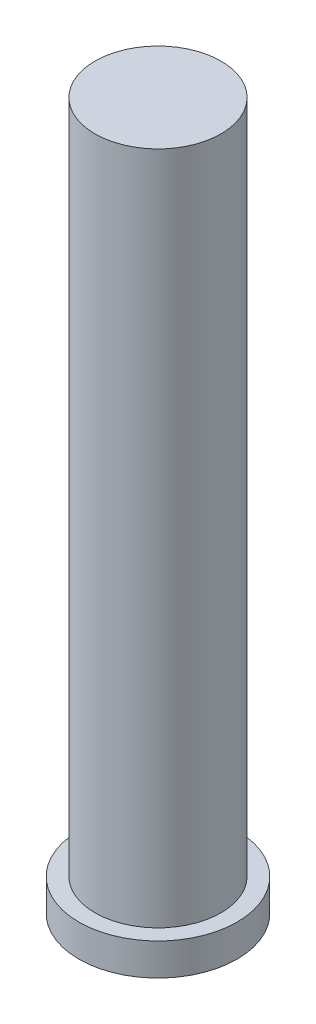
SolidWorks part; units mm, degrees
ref_plane "Ebene vorne" through (0, 0, 0) normal (0, 0, 1) x (1, 0, 0)
ref_plane "Ebene oben" through (0, 0, 0) normal (0, 1, 0) x (1, 0, 0)
ref_plane "Ebene rechts" through (0, 0, 0) normal (1, 0, 0) x (0, 0, -1)
sketch "Skizze1" plane through (0, 0, 0) normal (0, 1, 0) x (1, 0, 0)
  circle A0 centre (0, 0) radius 4.925
  dimension "D1" = 9.85
extrude "Aufsatz-Linear austragen1" add sketch "Skizze1" along normal blind 2
sketch "Skizze2" plane through (0, 2, 0) normal (0, 1, 0) x (1, 0, 0)
  circle A0 centre (0, 0) radius 3.925
  dimension "D1" = 7.85
extrude "Aufsatz-Linear austragen2" add sketch "Skizze2" along normal blind 42
